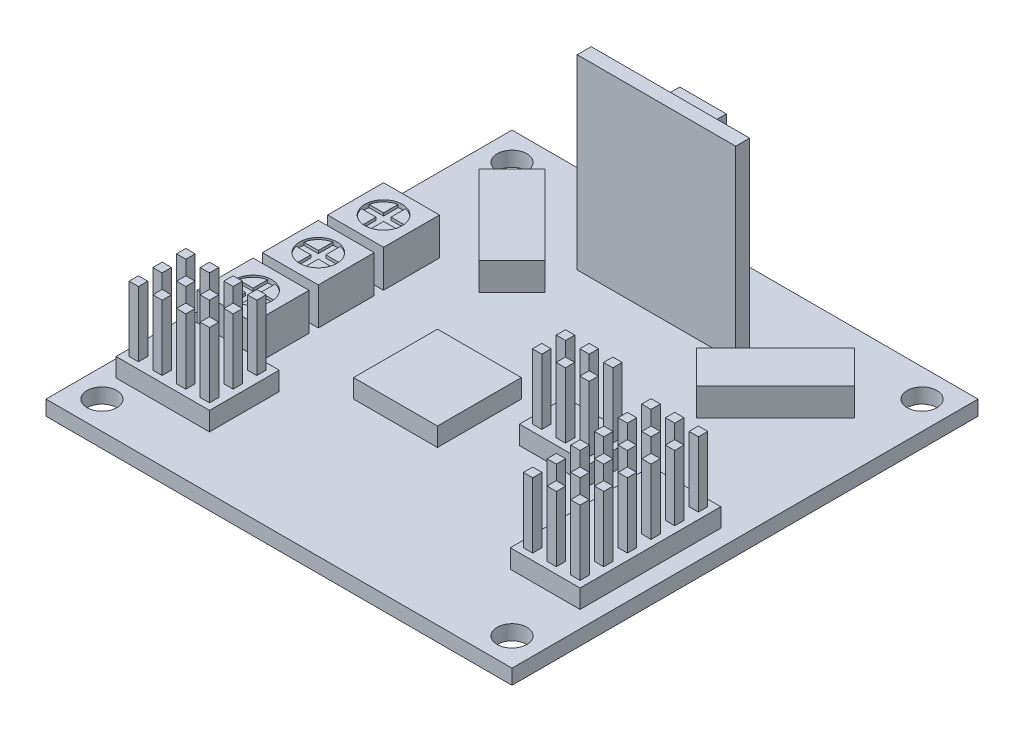
SolidWorks part; units mm, degrees
ref_plane "Front Plane" through (0, 0, 0) normal (0, 0, 1) x (1, 0, 0)
ref_plane "Top Plane" through (0, 0, 0) normal (0, 1, 0) x (1, 0, 0)
ref_plane "Right Plane" through (0, 0, 0) normal (1, 0, 0) x (0, 0, -1)
sketch "Sketch1" plane through (0, 0, 0) normal (0, 1, 0) x (1, 0, 0)
  line L1 (-25, -25) -> (25, -25)
  line L2 (-25, -25) -> (-25, 25)
  line L3 (-25, 25) -> (25, 25)
  line L4 (25, -25) -> (25, 25)
  line L5 (-25, -25) -> (25, 25) construction
  line L6 (-25, 25) -> (25, -25) construction
  circle A0 centre (-22, 22) radius 1.6
  circle A1 centre (22, 22) radius 1.6
  circle A2 centre (22, -22) radius 1.6
  circle A3 centre (-22, -22) radius 1.6
  point P0 (0, 0)
  point P17 (0, 0)
  dimension "D2" = 3.2
  dimension "D3" = 22
  dimension "D1" = 50
  dimension "D4" = 4
extrude "Boss-Extrude1" add sketch "Sketch1" along normal blind 1.6
sketch "Sketch2" plane through (0, 1.6, 0) normal (0, 1, 0) x (1, 0, 0)
  line L1 (-23, -3.7831) -> (-17, -3.7831)
  line L2 (-23, -3.7831) -> (-23, 2.2169)
  line L3 (-23, 2.2169) -> (-17, 2.2169)
  line L4 (-17, -3.7831) -> (-17, 2.2169)
  line L5 (-23, -3.7831) -> (-17, 2.2169) construction
  line L6 (-23, 2.2169) -> (-17, -3.7831) construction
  line L7 (-23, 3.2169) -> (-17, 3.2169)
  line L8 (-23, 3.2169) -> (-23, 9.2169)
  line L9 (-23, 9.2169) -> (-17, 9.2169)
  line L10 (-17, 3.2169) -> (-17, 9.2169)
  line L11 (-23, 3.2169) -> (-17, 9.2169) construction
  line L12 (-23, 9.2169) -> (-17, 3.2169) construction
  line L13 (-23, -10.7831) -> (-17, -10.7831)
  line L14 (-23, -10.7831) -> (-23, -4.7831)
  line L15 (-23, -4.7831) -> (-17, -4.7831)
  line L16 (-17, -10.7831) -> (-17, -4.7831)
  line L17 (-23, -10.7831) -> (-17, -4.7831) construction
  line L18 (-23, -4.7831) -> (-17, -10.7831) construction
  point P0 (-20, -0.7831)
  point P5 (-20, 6.2169)
  point P10 (-20, -7.7831)
  dimension "D1" = 20
  dimension "D2" = 6
  dimension "D3" = 1
  dimension "D4" = 1
extrude "Boss-Extrude2" add sketch "Sketch2" along normal blind 4
sketch "Sketch3" plane through (0, 5.6, 0) normal (0, 1, 0) x (1, 0, 0)
  circle A0 centre (-20, 6.2169) radius 2
  circle A1 centre (-20, -0.7831) radius 2
  circle A2 centre (-20, -7.7831) radius 2
  dimension "D1" = 4
extrude "Cut-Extrude1" cut sketch "Sketch3" against normal blind 0.2
sketch "Sketch4" plane through (0, 5.6, 0) normal (0, 1, 0) x (1, 0, 0)
  line L0 (-21.9596, 6.6169) -> (-20.4, 6.6169)
  line L1 (-20.4, 6.6169) -> (-20.4, 8.1764)
  line L2 (-19.6, 8.1764) -> (-19.6, 6.6169)
  line L3 (-19.6, 6.6169) -> (-18.0404, 6.6169)
  line L4 (-18.0404, 5.8169) -> (-19.6, 5.8169)
  line L5 (-19.6, 5.8169) -> (-19.6, 4.2573)
  line L6 (-20.4, 4.2573) -> (-20.4, 5.8169)
  line L7 (-20.4, 5.8169) -> (-21.9596, 5.8169)
  line L8 (-21.9596, -0.3831) -> (-20.4, -0.3831)
  line L9 (-20.4, -0.3831) -> (-20.4, 1.1764)
  line L10 (-19.6, 1.1764) -> (-19.6, -0.3831)
  line L11 (-19.6, -0.3831) -> (-18.0404, -0.3831)
  line L12 (-18.0404, -1.1831) -> (-19.6, -1.1831)
  line L13 (-19.6, -1.1831) -> (-19.6, -2.7427)
  line L14 (-20.4, -2.7427) -> (-20.4, -1.1831)
  line L15 (-20.4, -1.1831) -> (-21.9596, -1.1831)
  line L16 (-21.9596, -7.3831) -> (-20.4, -7.3831)
  line L17 (-20.4, -7.3831) -> (-20.4, -5.8236)
  line L18 (-19.6, -5.8236) -> (-19.6, -7.3831)
  line L19 (-19.6, -7.3831) -> (-18.0404, -7.3831)
  line L20 (-18.0404, -8.1831) -> (-19.6, -8.1831)
  line L21 (-19.6, -8.1831) -> (-19.6, -9.7427)
  line L22 (-20.4, -9.7427) -> (-20.4, -8.1831)
  line L23 (-20.4, -8.1831) -> (-21.9596, -8.1831)
  circle A0 centre (-20, 6.2169) radius 2 construction
  arc A1 (-21.9596, 6.6169) -> (-21.9596, 5.8169) centre (-20, 6.2169) ccw
  arc A2 (-19.6, 8.1764) -> (-20.4, 8.1764) centre (-20, 6.2169) ccw
  circle A3 centre (-20, 6.2169) radius 2
  arc A4 (-21.9596, 6.6169) -> (-21.9596, 5.8169) centre (-20, 6.2169) ccw
  arc A5 (-19.6, 8.1764) -> (-20.4, 8.1764) centre (-20, 6.2169) ccw
  arc A6 (-18.0404, 5.8169) -> (-18.0404, 6.6169) centre (-20, 6.2169) ccw
  arc A7 (-18.0404, 5.8169) -> (-18.0404, 6.6169) centre (-20, 6.2169) ccw
  arc A8 (-20.4, 4.2573) -> (-19.6, 4.2573) centre (-20, 6.2169) ccw
  arc A9 (-20.4, 4.2573) -> (-19.6, 4.2573) centre (-20, 6.2169) ccw
  arc A10 (-21.9596, -0.3831) -> (-21.9596, -1.1831) centre (-20, -0.7831) ccw
  arc A11 (-19.6, 1.1764) -> (-20.4, 1.1764) centre (-20, -0.7831) ccw
  arc A12 (-21.9596, -0.3831) -> (-21.9596, -1.1831) centre (-20, -0.7831) ccw
  arc A13 (-19.6, 1.1764) -> (-20.4, 1.1764) centre (-20, -0.7831) ccw
  arc A14 (-18.0404, -1.1831) -> (-18.0404, -0.3831) centre (-20, -0.7831) ccw
  arc A15 (-18.0404, -1.1831) -> (-18.0404, -0.3831) centre (-20, -0.7831) ccw
  arc A16 (-20.4, -2.7427) -> (-19.6, -2.7427) centre (-20, -0.7831) ccw
  arc A17 (-20.4, -2.7427) -> (-19.6, -2.7427) centre (-20, -0.7831) ccw
  arc A18 (-21.9596, -7.3831) -> (-21.9596, -8.1831) centre (-20, -7.7831) ccw
  arc A19 (-19.6, -5.8236) -> (-20.4, -5.8236) centre (-20, -7.7831) ccw
  arc A20 (-21.9596, -7.3831) -> (-21.9596, -8.1831) centre (-20, -7.7831) ccw
  arc A21 (-19.6, -5.8236) -> (-20.4, -5.8236) centre (-20, -7.7831) ccw
  arc A22 (-18.0404, -8.1831) -> (-18.0404, -7.3831) centre (-20, -7.7831) ccw
  arc A23 (-18.0404, -8.1831) -> (-18.0404, -7.3831) centre (-20, -7.7831) ccw
  arc A24 (-20.4, -9.7427) -> (-19.6, -9.7427) centre (-20, -7.7831) ccw
  arc A25 (-20.4, -9.7427) -> (-19.6, -9.7427) centre (-20, -7.7831) ccw
  point P21 (-20, 6.2169)
  point P33 (-20, -0.7831)
  point P48 (-20, -7.7831)
  circle M10 centre (-20, 6.2169) radius 2
  dimension "D3" = 0.8
  dimension "D1" = 0
  dimension "D4" = 3
  dimension "D2" = 4
extrude "Cut-Extrude2" cut sketch "Sketch4" against normal blind 0.5 contours L7 L6 L5 L4 L3 L2 L1 L0 M10 | L14 A16 L13 L12 A14 L11 L10 A11 L9 L8 A10 L15 | L22 A24 L21 L20 A22 L19 L18 A19 L17 L16 A18 L23
sketch "Sketch5" plane through (0, 1.6, 0) normal (0, 1, 0) x (1, 0, 0)
  line L0 (25, 25) -> (-25, 25) construction
  line L1 (-8.5, 15.5) -> (8.5, 15.5)
  line L2 (-8.5, 15.5) -> (-8.5, 17)
  line L3 (-8.5, 17) -> (8.5, 17)
  line L4 (8.5, 15.5) -> (8.5, 17)
  line L5 (-8.5, 15.5) -> (8.5, 17) construction
  line L6 (-8.5, 17) -> (8.5, 15.5) construction
  point P0 (0, 16.25)
  dimension "D1" = 17
  dimension "D2" = 0
  dimension "D3" = 8
  dimension "D4" = 1.5
extrude "Boss-Extrude3" add sketch "Sketch5" along normal blind 20
sketch "Sketch6" plane through (0, 1.6, 0) normal (0, 1, 0) x (1, 0, 0)
  line L0 (8.5, 17) -> (-8.5, 17) construction
  line L1 (-5.08, 18.5) -> (5.08, 18.5)
  line L2 (-5.08, 18.5) -> (-5.08, 15.5)
  line L3 (-5.08, 15.5) -> (5.08, 15.5)
  line L4 (5.08, 18.5) -> (5.08, 15.5)
  line L5 (-5.08, 18.5) -> (5.08, 15.5) construction
  line L6 (-5.08, 15.5) -> (5.08, 18.5) construction
  line L7 (-8.5, 15.5) -> (8.5, 15.5) construction
  point P0 (0, 17)
  dimension "D1" = 10.16
extrude "Boss-Extrude4" add sketch "Sketch6" along normal blind 2
sketch "Sketch7" plane through (0, 1.6, 0) normal (0, 1, 0) x (1, 0, 0)
  line L0 (0, 0) -> (-22, 22) construction
  line L1 (0, 0) -> (0, 25) construction
  line L2 (25, 25) -> (-25, 25) construction
  line L3 (-20.1525, 16.617) -> (-11.6673, 8.1317)
  line L4 (-20.1525, 16.617) -> (-16.617, 20.1525)
  line L5 (-11.6673, 8.1317) -> (-8.1317, 11.6673)
  line L6 (-16.617, 20.1525) -> (-8.1317, 11.6673)
  line L7 (-20.1525, 16.617) -> (-8.1317, 11.6673) construction
  line L8 (-11.6673, 8.1317) -> (-16.617, 20.1525) construction
  line L9 (11.6673, 8.1317) -> (16.617, 20.1525) construction
  line L10 (20.1525, 16.617) -> (8.1317, 11.6673) construction
  line L11 (16.617, 20.1525) -> (8.1317, 11.6673)
  line L12 (11.6673, 8.1317) -> (8.1317, 11.6673)
  line L13 (20.1525, 16.617) -> (16.617, 20.1525)
  line L14 (20.1525, 16.617) -> (11.6673, 8.1317)
  point P8 (-14.1421, 14.1421)
  point P16 (14.1421, 14.1421)
  dimension "D1" = 5
  dimension "D2" = 12
  dimension "D3" = 20
extrude "Boss-Extrude5" add sketch "Sketch7" along normal blind 3
sketch "Sketch8" plane through (0, 0, -17) normal (0, 0, -1) x (-1, 0, 0)
  line L0 (-8.5, 21.6) -> (-8.5, 1.6) construction
  line L1 (-3, 7.6) -> (2, 7.6)
  line L2 (-3, 7.6) -> (-3, 19.6)
  line L3 (-3, 19.6) -> (2, 19.6)
  line L4 (2, 7.6) -> (2, 19.6)
  line L5 (-3, 7.6) -> (2, 19.6) construction
  line L6 (-3, 19.6) -> (2, 7.6) construction
  line L7 (-8.5, 21.6) -> (8.5, 21.6) construction
  point P0 (-0.5, 13.6)
  dimension "D1" = 5
  dimension "D2" = 12
  dimension "D3" = 8
  dimension "D4" = 2
extrude "Boss-Extrude6" add sketch "Sketch8" along normal blind 3
sketch "Sketch9" plane through (0, 1.6, 0) normal (0, 1, 0) x (1, 0, 0)
  line L1 (-8.5, -8.5) -> (0.5, -8.5)
  line L2 (-8.5, -8.5) -> (-8.5, 0.5)
  line L3 (-8.5, 0.5) -> (0.5, 0.5)
  line L4 (0.5, -8.5) -> (0.5, 0.5)
  line L5 (-8.5, -8.5) -> (0.5, 0.5) construction
  line L6 (-8.5, 0.5) -> (0.5, -8.5) construction
  point P0 (-4, -4)
  point P8 (-4.7182, -3.3164)
  point P9 (-6.7205, -2.9682)
  dimension "D1" = 9
  dimension "D2" = 4
  dimension "D3" = 4
extrude "Boss-Extrude7" add sketch "Sketch9" along normal blind 2
sketch "Sketch10" plane through (0, 1.6, 0) normal (0, 1, 0) x (1, 0, 0)
  line L0 (-19.96, -13.5) -> (-18.96, -13.5)
  line L1 (-22.5, -13.5) -> (-21.5, -13.5)
  line L2 (-22.5, -13.5) -> (-22.5, -12.5)
  line L3 (-22.5, -12.5) -> (-21.5, -12.5)
  line L4 (-21.5, -13.5) -> (-21.5, -12.5)
  line L5 (-22.5, -13.5) -> (-21.5, -12.5) construction
  line L6 (-22.5, -12.5) -> (-21.5, -13.5) construction
  line L7 (-19.96, -13.5) -> (-19.96, -12.5)
  line L8 (-19.96, -12.5) -> (-18.96, -12.5)
  line L9 (-18.96, -13.5) -> (-18.96, -12.5)
  line L10 (-19.96, -13.5) -> (-18.96, -12.5) construction
  line L11 (-19.96, -12.5) -> (-18.96, -13.5) construction
  line L12 (-17.42, -13.5) -> (-16.42, -13.5)
  line L13 (-17.42, -13.5) -> (-17.42, -12.5)
  line L14 (-17.42, -12.5) -> (-16.42, -12.5)
  line L15 (-16.42, -13.5) -> (-16.42, -12.5)
  line L16 (-17.42, -13.5) -> (-16.42, -12.5) construction
  line L17 (-17.42, -12.5) -> (-16.42, -13.5) construction
  line L18 (-14.88, -13.5) -> (-13.88, -13.5)
  line L19 (-14.88, -13.5) -> (-14.88, -12.5)
  line L20 (-14.88, -12.5) -> (-13.88, -12.5)
  line L21 (-13.88, -13.5) -> (-13.88, -12.5)
  line L22 (-14.88, -13.5) -> (-13.88, -12.5) construction
  line L23 (-14.88, -12.5) -> (-13.88, -13.5) construction
  line L24 (-19.96, -16.04) -> (-18.96, -16.04)
  line L25 (-19.96, -16.04) -> (-19.96, -15.04)
  line L26 (-19.96, -15.04) -> (-18.96, -15.04)
  line L27 (-18.96, -16.04) -> (-18.96, -15.04)
  line L28 (-19.96, -16.04) -> (-18.96, -15.04) construction
  line L29 (-19.96, -15.04) -> (-18.96, -16.04) construction
  line L30 (-17.42, -16.04) -> (-16.42, -16.04)
  line L31 (-17.42, -16.04) -> (-17.42, -15.04)
  line L32 (-17.42, -15.04) -> (-16.42, -15.04)
  line L33 (-16.42, -16.04) -> (-16.42, -15.04)
  line L34 (-17.42, -16.04) -> (-16.42, -15.04) construction
  line L35 (-17.42, -15.04) -> (-16.42, -16.04) construction
  line L36 (-14.88, -16.04) -> (-13.88, -16.04)
  line L37 (-14.88, -16.04) -> (-14.88, -15.04)
  line L38 (-14.88, -15.04) -> (-13.88, -15.04)
  line L39 (-13.88, -16.04) -> (-13.88, -15.04)
  line L40 (-14.88, -16.04) -> (-13.88, -15.04) construction
  line L41 (-14.88, -15.04) -> (-13.88, -16.04) construction
  line L42 (-19.96, -18.58) -> (-18.96, -18.58)
  line L43 (-19.96, -18.58) -> (-19.96, -17.58)
  line L44 (-19.96, -17.58) -> (-18.96, -17.58)
  line L45 (-18.96, -18.58) -> (-18.96, -17.58)
  line L46 (-19.96, -18.58) -> (-18.96, -17.58) construction
  line L47 (-19.96, -17.58) -> (-18.96, -18.58) construction
  line L48 (-17.42, -18.58) -> (-16.42, -18.58)
  line L49 (-17.42, -18.58) -> (-17.42, -17.58)
  line L50 (-17.42, -17.58) -> (-16.42, -17.58)
  line L51 (-16.42, -18.58) -> (-16.42, -17.58)
  line L52 (-17.42, -18.58) -> (-16.42, -17.58) construction
  line L53 (-17.42, -17.58) -> (-16.42, -18.58) construction
  line L54 (-14.88, -18.58) -> (-13.88, -18.58)
  line L55 (-14.88, -18.58) -> (-14.88, -17.58)
  line L56 (-14.88, -17.58) -> (-13.88, -17.58)
  line L57 (-13.88, -18.58) -> (-13.88, -17.58)
  line L58 (-14.88, -18.58) -> (-13.88, -17.58) construction
  line L59 (-14.88, -17.58) -> (-13.88, -18.58) construction
  line L60 (-22.5, -16.04) -> (-21.5, -16.04)
  line L61 (-22.5, -16.04) -> (-22.5, -15.04)
  line L62 (-22.5, -15.04) -> (-21.5, -15.04)
  line L63 (-21.5, -16.04) -> (-21.5, -15.04)
  line L64 (-22.5, -16.04) -> (-21.5, -15.04) construction
  line L65 (-22.5, -15.04) -> (-21.5, -16.04) construction
  line L66 (-22.5, -18.58) -> (-21.5, -18.58)
  line L67 (-22.5, -18.58) -> (-22.5, -17.58)
  line L68 (-22.5, -17.58) -> (-21.5, -17.58)
  line L69 (-21.5, -18.58) -> (-21.5, -17.58)
  line L70 (-22.5, -18.58) -> (-21.5, -17.58) construction
  line L71 (-22.5, -17.58) -> (-21.5, -18.58) construction
  line L72 (-25, -25) -> (25, -25) construction
  line L73 (-25, 25) -> (-25, -25) construction
  line L74 (25, -25) -> (25, 25) construction
  line L75 (21.5, -2.5) -> (22.5, -2.5)
  line L76 (21.5, -2.5) -> (21.5, -1.5)
  line L77 (21.5, -1.5) -> (22.5, -1.5)
  line L78 (22.5, -2.5) -> (22.5, -1.5)
  line L79 (21.5, -2.5) -> (22.5, -1.5) construction
  line L80 (21.5, -1.5) -> (22.5, -2.5) construction
  line L81 (18.96, -2.5) -> (19.96, -2.5)
  line L82 (18.96, -2.5) -> (18.96, -1.5)
  line L83 (18.96, -1.5) -> (19.96, -1.5)
  line L84 (19.96, -2.5) -> (19.96, -1.5)
  line L85 (18.96, -2.5) -> (19.96, -1.5) construction
  line L86 (18.96, -1.5) -> (19.96, -2.5) construction
  line L87 (16.42, -2.5) -> (17.42, -2.5)
  line L88 (16.42, -2.5) -> (16.42, -1.5)
  line L89 (16.42, -1.5) -> (17.42, -1.5)
  line L90 (17.42, -2.5) -> (17.42, -1.5)
  line L91 (16.42, -2.5) -> (17.42, -1.5) construction
  line L92 (16.42, -1.5) -> (17.42, -2.5) construction
  line L93 (18.96, -5.04) -> (19.96, -5.04)
  line L94 (18.96, -5.04) -> (18.96, -4.04)
  line L95 (18.96, -4.04) -> (19.96, -4.04)
  line L96 (19.96, -5.04) -> (19.96, -4.04)
  line L97 (18.96, -5.04) -> (19.96, -4.04) construction
  line L98 (18.96, -4.04) -> (19.96, -5.04) construction
  line L99 (16.42, -5.04) -> (17.42, -5.04)
  line L100 (16.42, -5.04) -> (16.42, -4.04)
  line L101 (16.42, -4.04) -> (17.42, -4.04)
  line L102 (17.42, -5.04) -> (17.42, -4.04)
  line L103 (16.42, -5.04) -> (17.42, -4.04) construction
  line L104 (16.42, -4.04) -> (17.42, -5.04) construction
  line L105 (18.96, -7.58) -> (19.96, -7.58)
  line L106 (18.96, -7.58) -> (18.96, -6.58)
  line L107 (18.96, -6.58) -> (19.96, -6.58)
  line L108 (19.96, -7.58) -> (19.96, -6.58)
  line L109 (18.96, -7.58) -> (19.96, -6.58) construction
  line L110 (18.96, -6.58) -> (19.96, -7.58) construction
  line L111 (16.42, -7.58) -> (17.42, -7.58)
  line L112 (16.42, -7.58) -> (16.42, -6.58)
  line L113 (16.42, -6.58) -> (17.42, -6.58)
  line L114 (17.42, -7.58) -> (17.42, -6.58)
  line L115 (16.42, -7.58) -> (17.42, -6.58) construction
  line L116 (16.42, -6.58) -> (17.42, -7.58) construction
  line L117 (18.96, -10.12) -> (19.96, -10.12)
  line L118 (18.96, -10.12) -> (18.96, -9.12)
  line L119 (18.96, -9.12) -> (19.96, -9.12)
  line L120 (19.96, -10.12) -> (19.96, -9.12)
  line L121 (18.96, -10.12) -> (19.96, -9.12) construction
  line L122 (18.96, -9.12) -> (19.96, -10.12) construction
  line L123 (16.42, -10.12) -> (17.42, -10.12)
  line L124 (16.42, -10.12) -> (16.42, -9.12)
  line L125 (16.42, -9.12) -> (17.42, -9.12)
  line L126 (17.42, -10.12) -> (17.42, -9.12)
  line L127 (16.42, -10.12) -> (17.42, -9.12) construction
  line L128 (16.42, -9.12) -> (17.42, -10.12) construction
  line L129 (18.96, -12.66) -> (19.96, -12.66)
  line L130 (18.96, -12.66) -> (18.96, -11.66)
  line L131 (18.96, -11.66) -> (19.96, -11.66)
  line L132 (19.96, -12.66) -> (19.96, -11.66)
  line L133 (18.96, -12.66) -> (19.96, -11.66) construction
  line L134 (18.96, -11.66) -> (19.96, -12.66) construction
  line L135 (16.42, -12.66) -> (17.42, -12.66)
  line L136 (16.42, -12.66) -> (16.42, -11.66)
  line L137 (16.42, -11.66) -> (17.42, -11.66)
  line L138 (17.42, -12.66) -> (17.42, -11.66)
  line L139 (16.42, -12.66) -> (17.42, -11.66) construction
  line L140 (16.42, -11.66) -> (17.42, -12.66) construction
  line L141 (18.96, -15.2) -> (19.96, -15.2)
  line L142 (18.96, -15.2) -> (18.96, -14.2)
  line L143 (18.96, -14.2) -> (19.96, -14.2)
  line L144 (19.96, -15.2) -> (19.96, -14.2)
  line L145 (18.96, -15.2) -> (19.96, -14.2) construction
  line L146 (18.96, -14.2) -> (19.96, -15.2) construction
  line L147 (16.42, -15.2) -> (17.42, -15.2)
  line L148 (16.42, -15.2) -> (16.42, -14.2)
  line L149 (16.42, -14.2) -> (17.42, -14.2)
  line L150 (17.42, -15.2) -> (17.42, -14.2)
  line L151 (16.42, -15.2) -> (17.42, -14.2) construction
  line L152 (16.42, -14.2) -> (17.42, -15.2) construction
  line L153 (21.5, -5.04) -> (22.5, -5.04)
  line L154 (21.5, -5.04) -> (21.5, -4.04)
  line L155 (21.5, -4.04) -> (22.5, -4.04)
  line L156 (22.5, -5.04) -> (22.5, -4.04)
  line L157 (21.5, -5.04) -> (22.5, -4.04) construction
  line L158 (21.5, -4.04) -> (22.5, -5.04) construction
  line L159 (21.5, -7.58) -> (22.5, -7.58)
  line L160 (21.5, -7.58) -> (21.5, -6.58)
  line L161 (21.5, -6.58) -> (22.5, -6.58)
  line L162 (22.5, -7.58) -> (22.5, -6.58)
  line L163 (21.5, -7.58) -> (22.5, -6.58) construction
  line L164 (21.5, -6.58) -> (22.5, -7.58) construction
  line L165 (21.5, -10.12) -> (22.5, -10.12)
  line L166 (21.5, -10.12) -> (21.5, -9.12)
  line L167 (21.5, -9.12) -> (22.5, -9.12)
  line L168 (22.5, -10.12) -> (22.5, -9.12)
  line L169 (21.5, -10.12) -> (22.5, -9.12) construction
  line L170 (21.5, -9.12) -> (22.5, -10.12) construction
  line L171 (21.5, -12.66) -> (22.5, -12.66)
  line L172 (21.5, -12.66) -> (21.5, -11.66)
  line L173 (21.5, -11.66) -> (22.5, -11.66)
  line L174 (22.5, -12.66) -> (22.5, -11.66)
  line L175 (21.5, -12.66) -> (22.5, -11.66) construction
  line L176 (21.5, -11.66) -> (22.5, -12.66) construction
  line L177 (21.5, -15.2) -> (22.5, -15.2)
  line L178 (21.5, -15.2) -> (21.5, -14.2)
  line L179 (21.5, -14.2) -> (22.5, -14.2)
  line L180 (22.5, -15.2) -> (22.5, -14.2)
  line L181 (21.5, -15.2) -> (22.5, -14.2) construction
  line L182 (21.5, -14.2) -> (22.5, -15.2) construction
  line L183 (7.96, -0.6823) -> (8.96, -0.6823)
  line L184 (10.5, -0.6823) -> (11.5, -0.6823)
  line L185 (10.5, -0.6823) -> (10.5, 0.3177)
  line L186 (10.5, 0.3177) -> (11.5, 0.3177)
  line L187 (11.5, -0.6823) -> (11.5, 0.3177)
  line L188 (10.5, -0.6823) -> (11.5, 0.3177) construction
  line L189 (10.5, 0.3177) -> (11.5, -0.6823) construction
  line L190 (7.96, -0.6823) -> (7.96, 0.3177)
  line L191 (7.96, 0.3177) -> (8.96, 0.3177)
  line L192 (8.96, -0.6823) -> (8.96, 0.3177)
  line L193 (7.96, -0.6823) -> (8.96, 0.3177) construction
  line L194 (7.96, 0.3177) -> (8.96, -0.6823) construction
  line L195 (5.42, -0.6823) -> (6.42, -0.6823)
  line L196 (5.42, -0.6823) -> (5.42, 0.3177)
  line L197 (5.42, 0.3177) -> (6.42, 0.3177)
  line L198 (6.42, -0.6823) -> (6.42, 0.3177)
  line L199 (5.42, -0.6823) -> (6.42, 0.3177) construction
  line L200 (5.42, 0.3177) -> (6.42, -0.6823) construction
  line L201 (7.96, -3.2223) -> (8.96, -3.2223)
  line L202 (7.96, -3.2223) -> (7.96, -2.2223)
  line L203 (7.96, -2.2223) -> (8.96, -2.2223)
  line L204 (8.96, -3.2223) -> (8.96, -2.2223)
  line L205 (7.96, -3.2223) -> (8.96, -2.2223) construction
  line L206 (7.96, -2.2223) -> (8.96, -3.2223) construction
  line L207 (5.42, -3.2223) -> (6.42, -3.2223)
  line L208 (5.42, -3.2223) -> (5.42, -2.2223)
  line L209 (5.42, -2.2223) -> (6.42, -2.2223)
  line L210 (6.42, -3.2223) -> (6.42, -2.2223)
  line L211 (5.42, -3.2223) -> (6.42, -2.2223) construction
  line L212 (5.42, -2.2223) -> (6.42, -3.2223) construction
  line L213 (10.5, -3.2223) -> (11.5, -3.2223)
  line L214 (10.5, -3.2223) -> (10.5, -2.2223)
  line L215 (10.5, -2.2223) -> (11.5, -2.2223)
  line L216 (11.5, -3.2223) -> (11.5, -2.2223)
  line L217 (10.5, -3.2223) -> (11.5, -2.2223) construction
  line L218 (10.5, -2.2223) -> (11.5, -3.2223) construction
  point P0 (-22, -13)
  point P8 (-19.46, -13)
  point P13 (-16.92, -13)
  point P18 (-14.38, -13)
  point P23 (-19.46, -15.54)
  point P28 (-16.92, -15.54)
  point P33 (-14.38, -15.54)
  point P38 (-19.46, -18.08)
  point P43 (-16.92, -18.08)
  point P48 (-14.38, -18.08)
  point P53 (-22, -15.54)
  point P58 (-22, -18.08)
  point P64 (22, -2)
  point P71 (11, -0.1823)
  point P73 (19.46, -2)
  point P78 (16.92, -2)
  point P83 (19.46, -4.54)
  point P88 (16.92, -4.54)
  point P93 (19.46, -7.08)
  point P98 (16.92, -7.08)
  point P103 (19.46, -9.62)
  point P108 (16.92, -9.62)
  point P113 (19.46, -12.16)
  point P118 (16.92, -12.16)
  point P123 (19.46, -14.7)
  point P128 (16.92, -14.7)
  point P133 (22, -4.54)
  point P138 (22, -7.08)
  point P143 (22, -9.62)
  point P148 (22, -12.16)
  point P153 (22, -14.7)
  point P165 (8.46, -0.1823)
  point P170 (5.92, -0.1823)
  point P175 (8.46, -2.7223)
  point P180 (5.92, -2.7223)
  point P185 (11, -2.7223)
  dimension "D1" = 1
  dimension "D2" = 1
  dimension "D5" = 12
  dimension "D6" = 3
  dimension "D7" = 3
  dimension "D10" = 2
  dimension "D11" = 14
  dimension "D3" = 4
  dimension "D4" = 3
  dimension "D8" = 3
  dimension "D9" = 6
  dimension "D12" = 3
  dimension "D13" = 2
extrude "Boss-Extrude8" add sketch "Sketch10" along normal blind 9
sketch "Sketch11" plane through (0, 1.6, 0) normal (0, 1, 0) x (1, 0, 0)
  line L0 (-21.5, -12.5) -> (-22.5, -12.5) construction
  line L1 (-23.2, -11.8) -> (-13.18, -11.8)
  line L2 (-23.2, -11.8) -> (-23.2, -19.28)
  line L3 (-23.2, -19.28) -> (-13.18, -19.28)
  line L4 (-13.18, -11.8) -> (-13.18, -19.28)
  line L5 (-22.5, -12.5) -> (-22.5, -13.5) construction
  line L6 (-14.88, -18.58) -> (-13.88, -18.58) construction
  line L7 (-13.88, -18.58) -> (-13.88, -17.58) construction
  line L8 (5.42, 0.3177) -> (5.42, -0.6823) construction
  line L9 (4.72, -3.9223) -> (12.2, -3.9223)
  line L10 (4.72, -3.9223) -> (4.72, 1.0177)
  line L11 (4.72, 1.0177) -> (12.2, 1.0177)
  line L12 (12.2, -3.9223) -> (12.2, 1.0177)
  line L13 (5.42, -3.2223) -> (6.42, -3.2223) construction
  line L14 (8.96, 0.3177) -> (7.96, 0.3177) construction
  line L15 (11.5, -0.6823) -> (11.5, 0.3177) construction
  line L16 (16.42, -1.5) -> (16.42, -2.5) construction
  line L17 (15.72, -0.8) -> (23.2, -0.8)
  line L18 (15.72, -0.8) -> (15.72, -15.9)
  line L19 (15.72, -15.9) -> (23.2, -15.9)
  line L20 (23.2, -0.8) -> (23.2, -15.9)
  line L21 (17.42, -1.5) -> (16.42, -1.5) construction
  line L22 (16.42, -15.2) -> (17.42, -15.2) construction
  line L23 (22.5, -15.2) -> (22.5, -14.2) construction
  point P6 (-22.5, -13)
  point P11 (-13.88, -18.08)
  point P18 (5.42, -0.1823)
  point P23 (8.46, 0.3177)
  point P32 (16.42, -2)
  point P37 (16.92, -15.2)
  point P40 (22.5, -14.7)
  dimension "D1" = 0.7
  dimension "D2" = 0.7
  dimension "D3" = 0.7
  dimension "D4" = 0.7
  dimension "D5" = 0.7
  dimension "D6" = 0.7
  dimension "D7" = 0.7
  dimension "D8" = 0.7
  dimension "D9" = 0.7
  dimension "D10" = 0.7
  dimension "D11" = 0.7
  dimension "D12" = 0.7
extrude "Boss-Extrude10" add sketch "Sketch11" along normal blind 2
